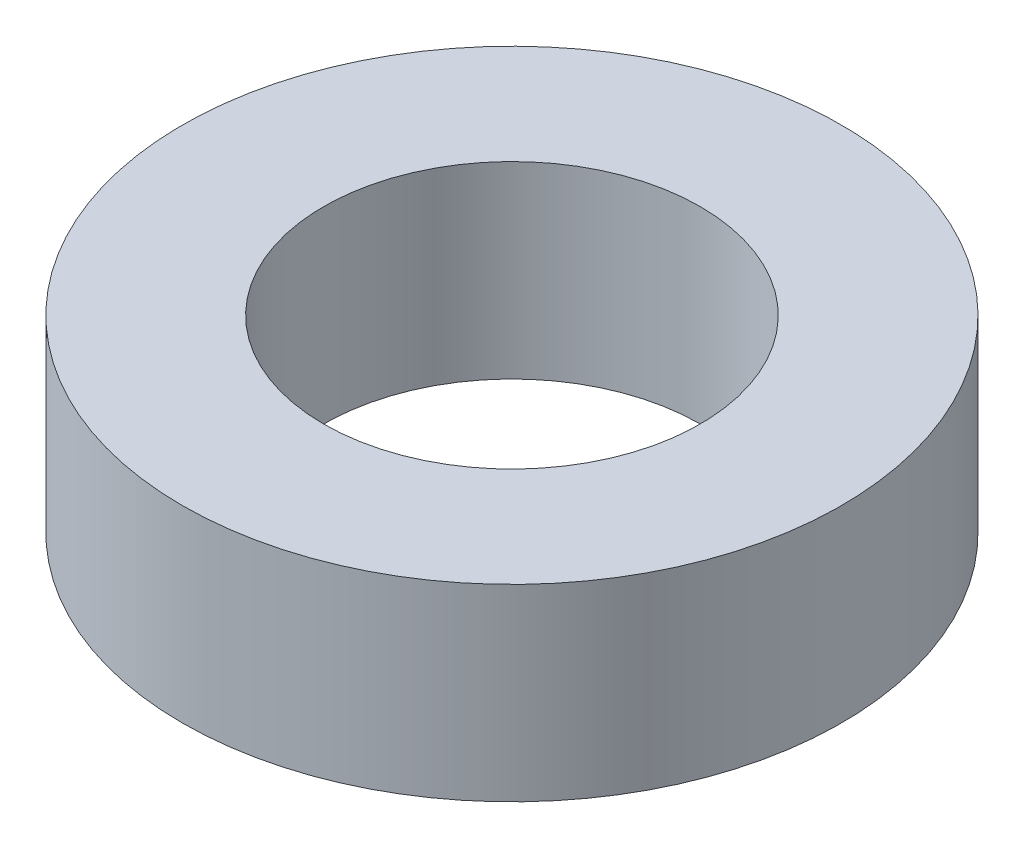
SolidWorks part; units mm, degrees
ref_plane "前视基准面" through (0, 0, 0) normal (0, 0, 1) x (1, 0, 0)
ref_plane "上视基准面" through (0, 0, 0) normal (0, 1, 0) x (1, 0, 0)
ref_plane "右视基准面" through (0, 0, 0) normal (1, 0, 0) x (0, 0, -1)
sketch "草图1" plane through (0, 0, 0) normal (0, 1, 0) x (1, 0, 0)
  circle A0 centre (0, 0) radius 7
  circle A1 centre (0, 0) radius 4
  dimension "D1" = 14
  dimension "D2" = 8
extrude "凸台-拉伸1" add sketch "草图1" along normal blind 4
